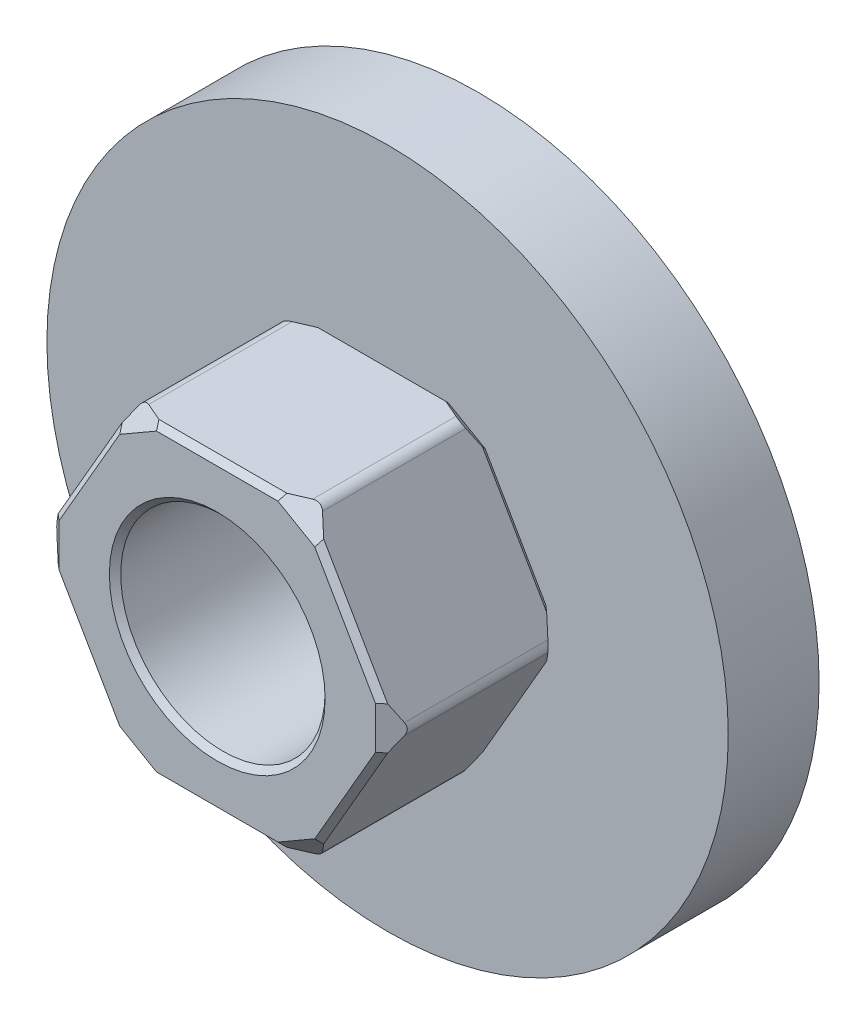
SolidWorks part; units mm, degrees
ref_plane "Front Plane" through (0, 0, 0) normal (0, 0, 1) x (1, 0, 0)
ref_plane "Top Plane" through (0, 0, 0) normal (0, 1, 0) x (1, 0, 0)
ref_plane "Right Plane" through (0, 0, 0) normal (1, 0, 0) x (0, 0, -1)
sketch "Sketch1" plane through (0, 0, 0) normal (0, 0, 1) x (1, 0, 0)
  line L1 (-7.7942, 13.5) -> (-15.5885, 0)
  line L2 (-15.5885, 0) -> (-7.7942, -13.5)
  line L3 (-7.7942, -13.5) -> (7.7942, -13.5)
  line L4 (7.7942, -13.5) -> (15.5885, 0)
  line L5 (15.5885, 0) -> (7.7942, 13.5)
  line L6 (7.7942, 13.5) -> (-7.7942, 13.5)
  circle A0 centre (0, 0) radius 9
  circle A1 centre (0, 0) radius 13.5 construction
  dimension "D1" = 18
  dimension "D2" = 27
extrude "Boss-Extrude1" add sketch "Sketch1" along normal blind 15
chamfer "Chamfer1" distance 0.5 angle 45 14 edges at (9, 0, 0) (-11.6913, 6.75, 0) (-11.6913, -6.75, 0) (0, -13.5, 0) (11.6913, -6.75, 0) (11.6913, 6.75, 0) (0, 13.5, 0) (9, 0, 15) (11.6913, 6.75, 15) (11.6913, -6.75, 15) (0, -13.5, 15) (-11.6913, -6.75, 15) (-11.6913, 6.75, 15) (0, 13.5, 15)
chamfer "Chamfer2" distance 2 12 edges at (-15.2998, 0, 14.75) (-7.6499, -13.25, 14.75) (7.6499, -13.25, 14.75) (15.2998, 0, 14.75) (7.6499, 13.25, 14.75) (-7.6499, 13.25, 14.75) (-7.6499, 13.25, 0.25) (7.6499, 13.25, 0.25) (-15.2998, 0, 0.25) (-7.6499, -13.25, 0.25) (7.6499, -13.25, 0.25) (15.2998, 0, 0.25)
fillet "Fillet1" radius 1 6 edges at (-7.7942, 13.5, 7.5) (7.7942, 13.5, 7.5) (15.5885, 0, 7.5) (7.7942, -13.5, 7.5) (-7.7942, -13.5, 7.5) (-15.5885, 0, 7.5)
sketch "Sketch2" plane through (0, 0, 0) normal (0, 0, -1) x (-1, 0, 0)
  circle A0 centre (0, 0) radius 30
  circle A1 centre (0, 0) radius 9
  dimension "D1" = 18
  dimension "D2" = 60
extrude "Boss-Extrude2" add sketch "Sketch2" along normal blind 8 separate body
